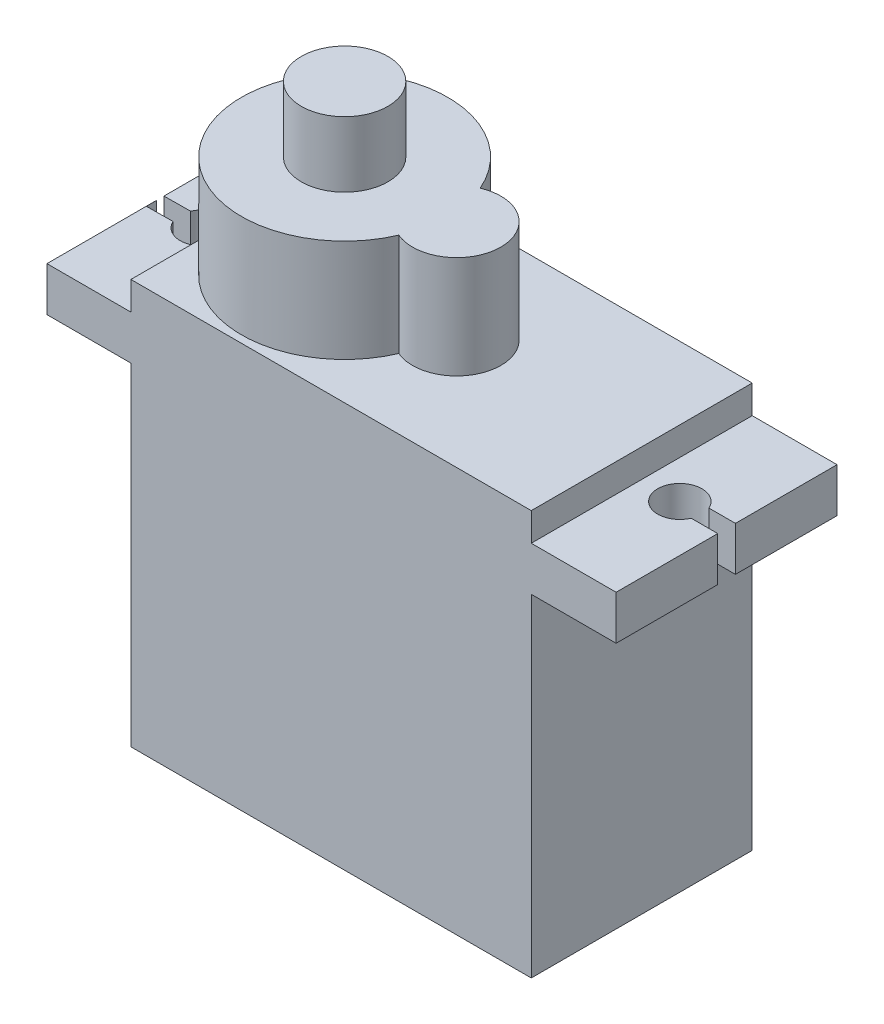
SolidWorks part; units mm, degrees
ref_plane "Front Plane" through (0, 0, 0) normal (0, 0, 1) x (1, 0, 0)
ref_plane "Top Plane" through (0, 0, 0) normal (0, 1, 0) x (1, 0, 0)
ref_plane "Right Plane" through (0, 0, 0) normal (1, 0, 0) x (0, 0, -1)
sketch "Sketch1" plane through (0, 0, 0) normal (0, 1, 0) x (1, 0, 0)
  line L1 (-46.1955, 5.2431) -> (-23.5455, 5.2431)
  line L2 (-46.1955, 5.2431) -> (-46.1955, -7.2569)
  line L3 (-46.1955, -7.2569) -> (-23.5455, -7.2569)
  line L4 (-23.5455, 5.2431) -> (-23.5455, -7.2569)
  dimension "D1" = 22.65
  dimension "D2" = 12.5
extrude "Boss-Extrude1" add sketch "Sketch1" along normal blind 22.9
ref_plane "Plane1" through (-23.5455, 22.9, -5.2431) normal (0, -1, 0) x (1, 0, 0)
ref_plane "Plane2" through (-46.1955, 22.9, -5.2431) normal (0, 0, 1) x (1, 0, 0)
sketch "Sketch4" plane through (0, 22.9, 0) normal (0, 1, 0) x (-1, 0, 0)
  line L0 (46.1955, 1.0069) -> (40.3555, 1.0069)
  line L1 (46.1955, -5.2431) -> (46.1955, 7.2569) construction
  circle A0 centre (40.3555, 1.0069) radius 5.84
extrude "Boss-Extrude6" add sketch "Sketch4" along normal blind 5.8
sketch "Sketch12" plane through (0, 28.7, 0) normal (0, 1, 0) x (-1, 0, 0)
  circle A0 centre (40.3555, 1.0069) radius 2.45
extrude "Boss-Extrude7" add sketch "Sketch12" along normal blind 3.7
sketch "Sketch13" plane through (0, 22.9, 0) normal (0, 1, 0) x (-1, 0, 0)
  line L0 (34.5155, 1.0069) -> (34.0155, 1.0069)
  circle A0 centre (40.3555, 1.0069) radius 5.84 construction
  circle A1 centre (34.0155, 1.0069) radius 2.5
extrude "Boss-Extrude8" add sketch "Sketch13" along normal blind 5.8
sketch "Sketch16" plane through (-23.5455, 0, 0) normal (1, 0, 0) x (0, 0, -1)
  line L0 (-7.2569, 22.9) -> (-7.2569, 0) construction
  line L1 (-7.2569, 18.8) -> (5.2431, 18.8)
  line L2 (-7.2569, 18.8) -> (-7.2569, 21.3)
  line L3 (-7.2569, 21.3) -> (5.2431, 21.3)
  line L4 (5.2431, 18.8) -> (5.2431, 21.3)
  line L5 (5.2431, 22.9) -> (5.2431, 0) construction
  line L6 (-7.2569, 22.9) -> (5.2431, 22.9) construction
  dimension "D1" = 1.6
  dimension "D2" = 2.5
extrude "Boss-Extrude9" add sketch "Sketch16" along normal blind 4.8 and the other way blind 27.4
sketch "Sketch17" plane through (-23.5455, 22.9, -5.2431) normal (0, -1, 0) x (1, 0, 0)
  line L0 (-27.4, 6.25) -> (4.8, 6.25) construction
  line L1 (-27.4, 0) -> (-27.4, 12.5) construction
  line L2 (4.8, 0) -> (4.8, 12.5) construction
  line L3 (4.8, 6.25) -> (-11.3, 6.25) construction
  line L4 (-11.3, 6.25) -> (-11.325, 0) construction
  line L5 (0, 0) -> (-22.65, 0) construction
  line L6 (4.8, 5.75) -> (3.3, 5.75)
  line L7 (4.8, 6.75) -> (3.3, 6.75)
  line L9 (4.8, 5.75) -> (4.8, 6.75)
  line L10 (-27.3955, 6.8788) -> (-25.8955, 6.8668)
  line L11 (-27.4035, 5.8788) -> (-27.3955, 6.8788)
  line L12 (-27.4035, 5.8788) -> (-25.9035, 5.8668)
  arc A0 (3.3, 5.75) -> (3.3, 6.75) centre (2.1544, 6.25) cw
  arc A1 (-25.9035, 5.8668) -> (-25.8955, 6.8668) centre (-24.7539, 6.3576) ccw
  dimension "D3" = 1.25
  dimension "D1" = 1.5
  dimension "D2" = 0.5
extrude "Cut-Extrude2" cut sketch "Sketch17" along direction (0, 1, 0) on the side of the normal up to surface (4.1 mm away)
sketch "Sketch18" plane through (-46.1955, 0, 0) normal (-1, 0, 0) x (0, 0, 1)
  line L0 (-5.2431, 0) -> (7.2569, 0) construction
  line L1 (7.2569, 18.8) -> (7.2569, 0) construction
  line L4 (-5.2431, 18.8) -> (-5.2431, 0) construction
  circle A0 centre (1.0069, 5.15) radius 0.6
  circle A1 centre (-0.1931, 5.15) radius 0.6
  circle A2 centre (2.2069, 5.15) radius 0.6
  point P0 (1.0069, 0)
  dimension "D2" = 6.25
  dimension "D3" = 1.2
  dimension "D4" = 5.05
  dimension "D5" = 5.05
  dimension "D1" = 5.15
extrude "Boss-Extrude14" add sketch "Sketch18" along normal blind 1.5 separate body contours A1 | A0 | A2
